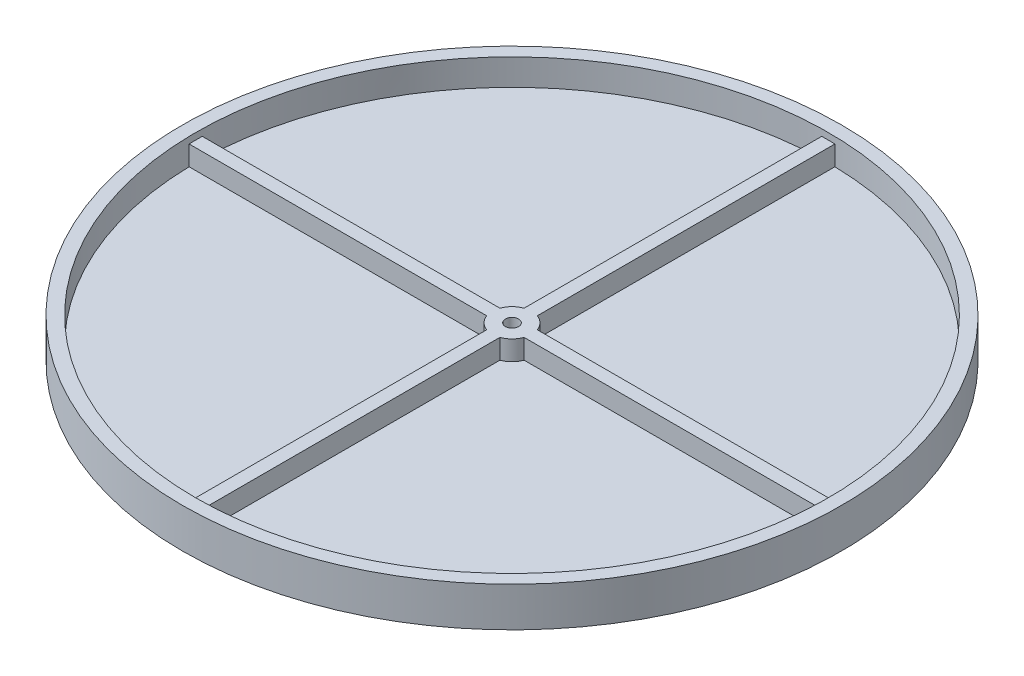
SolidWorks part; units mm, degrees
ref_plane "Alzado" through (0, 0, 0) normal (0, 0, 1) x (1, 0, 0)
ref_plane "Planta" through (0, 0, 0) normal (0, 1, 0) x (1, 0, 0)
ref_plane "Vista lateral" through (0, 0, 0) normal (1, 0, 0) x (0, 0, -1)
sketch "Croquis1" plane through (0, 0, 0) normal (0, 1, 0) x (1, 0, 0)
  circle A0 centre (0, 0) radius 250
  dimension "D1" = 500
extrude "Saliente-Extruir1" add sketch "Croquis1" along normal blind 10
sketch "Croquis2" plane through (0, 10, 0) normal (0, 1, 0) x (1, 0, 0)
  circle A0 centre (0, 0) radius 250
  circle A1 centre (0, 0) radius 240
  circle A2 centre (0, 0) radius 250 construction
  dimension "D1" = 10
extrude "Saliente-Extruir2" add sketch "Croquis2" along normal blind 20
sketch "Croquis3" plane through (0, 10, 0) normal (0, 1, 0) x (1, 0, 0)
  circle A0 centre (0, 0) radius 15
  dimension "D1" = 30
extrude "Saliente-Extruir3" add sketch "Croquis3" along normal blind 15
sketch "Croquis4" plane through (0, 25, 0) normal (0, 1, 0) x (1, 0, 0)
  circle A0 centre (0, 0) radius 5
  dimension "D1" = 10
extrude "Cortar-Extruir1" cut sketch "Croquis4" against normal through all
sketch "Croquis5" plane through (0, 10, 0) normal (0, 1, 0) x (1, 0, 0)
  line L0 (0, 240) -> (0, -240) construction
  line L1 (-240, 0) -> (240, 0) construction
  line L2 (9.1406, 5) -> (9.1406, -5)
  line L3 (9.1406, 5) -> (244.1847, 5)
  line L4 (244.1847, 5) -> (244.1847, -5)
  line L5 (244.1847, -5) -> (9.1406, -5)
  line L6 (5, -9.1406) -> (5, -244.1847)
  line L7 (-5, -244.1847) -> (-5, -9.1406)
  line L8 (5, -244.1847) -> (-5, -244.1847)
  line L9 (5, -9.1406) -> (-5, -9.1406)
  line L10 (-9.1406, -5) -> (-244.1847, -5)
  line L11 (-244.1847, 5) -> (-9.1406, 5)
  line L12 (-244.1847, -5) -> (-244.1847, 5)
  line L13 (-9.1406, -5) -> (-9.1406, 5)
  line L14 (-5, 9.1406) -> (-5, 244.1847)
  line L15 (5, 244.1847) -> (5, 9.1406)
  line L16 (-5, 244.1847) -> (5, 244.1847)
  line L17 (-5, 9.1406) -> (5, 9.1406)
  circle A0 centre (0, 0) radius 240 construction
  circle A1 centre (0, 0) radius 240 construction
  point P11 (9.1406, 0)
  point P29 (0, 0)
  dimension "D1" = 10
  dimension "D2" = 4
extrude "Saliente-Extruir4" add sketch "Croquis5" along normal up to surface (15 mm away) up to face at (0, 25, 5)
sketch "Croquis6" plane through (0, 10, 0) normal (0, 1, 0) x (1, 0, 0)
  line L0 (239.9479, -5) -> (5, -5) construction
  line L1 (5, -5) -> (5, -239.9479) construction
  line L6 (5, -239.9479) -> (5, -14.1421) construction
  line L7 (14.1421, -5) -> (239.9479, -5) construction
  dimension "D1" = 234.9479
sketch "Croquis8" plane through (0, 0, 0) normal (0, 0, 1) x (1, 0, 0)
  line L0 (0, 0) -> (0, 30) construction
  line L1 (240, 30) -> (-240, 30) construction
